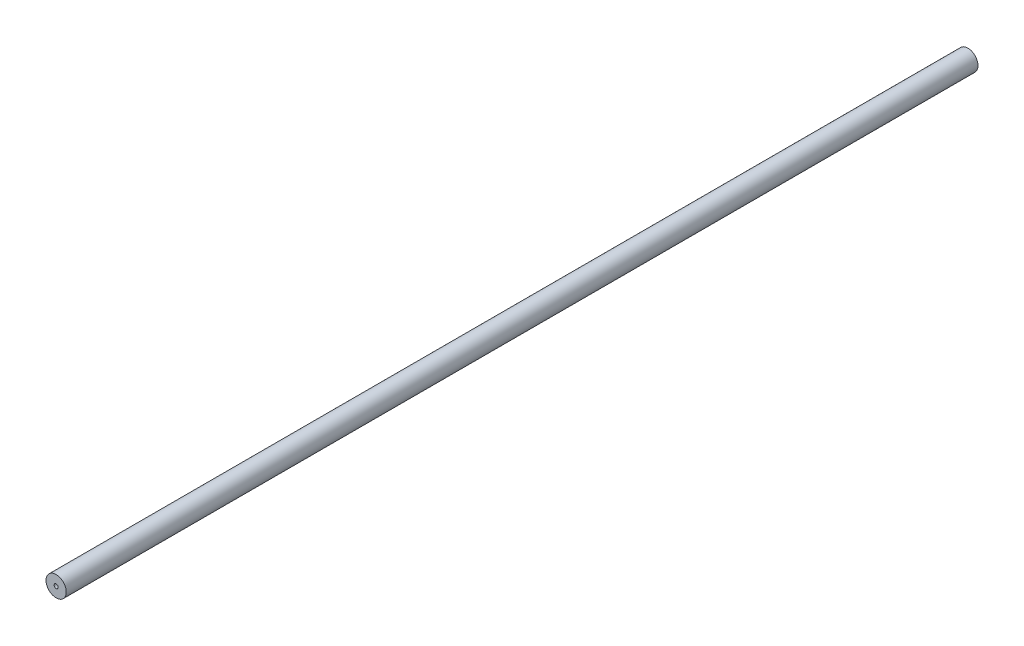
SolidWorks part; units mm, degrees
ref_plane "Alzado" through (0, 0, 0) normal (0, 0, 1) x (1, 0, 0)
ref_plane "Planta" through (0, 0, 0) normal (0, 1, 0) x (1, 0, 0)
ref_plane "Vista lateral" through (0, 0, 0) normal (1, 0, 0) x (0, 0, -1)
sketch "Croquis1" plane through (0, 0, 0) normal (0, 0, 1) x (1, 0, 0)
  circle A0 centre (0, 0) radius 2
  circle A1 centre (0, 0) radius 0.4
  dimension "D1" = 4
  dimension "D2" = 0.8
extrude "Saliente-Extruir1" add sketch "Croquis1" along normal blind 180
